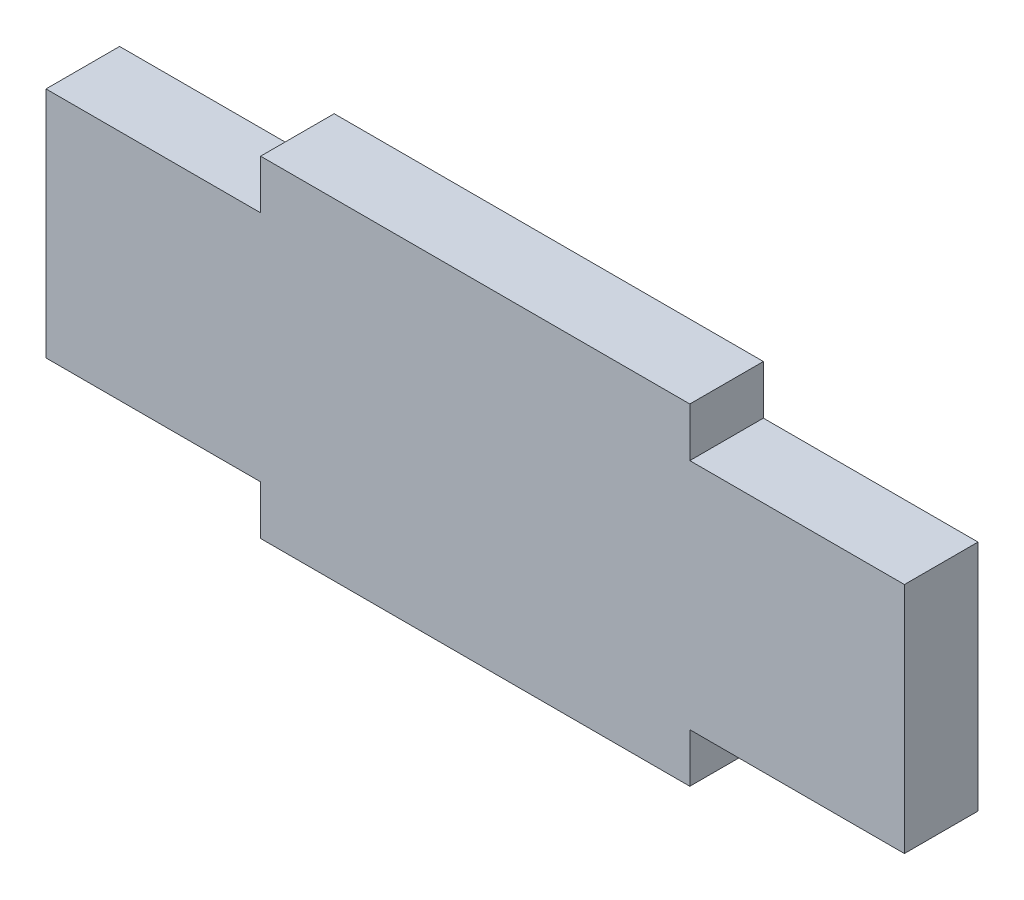
SolidWorks part; units mm, degrees
material "Acrílico (médio-alto impacto)"
ref_plane "Plano frontal" through (0, 0, 0) normal (0, 0, 1) x (1, 0, 0)
ref_plane "Plano superior" through (0, 0, 0) normal (0, 1, 0) x (1, 0, 0)
ref_plane "Plano direito" through (0, 0, 0) normal (1, 0, 0) x (0, 0, -1)
sketch "Esboço1" plane through (0, 0, 0) normal (0, 0, 1) x (1, 0, 0)
  line L0 (0, 0) -> (35, 0) construction
  line L1 (-35, -9.5) -> (35, -9.5)
  line L2 (-35, -9.5) -> (-35, 9.5)
  line L3 (-35, 9.5) -> (35, 9.5)
  line L4 (35, -9.5) -> (35, 9.5)
  line L5 (-35, -9.5) -> (35, 9.5) construction
  line L6 (-35, 9.5) -> (35, -9.5) construction
  line L7 (17.5, 13.5) -> (-17.5, 13.5)
  line L8 (17.5, 13.5) -> (17.5, 9.5)
  line L9 (17.5, 9.5) -> (-17.5, 9.5)
  line L10 (-17.5, 13.5) -> (-17.5, 9.5)
  line L11 (17.5, 13.5) -> (-17.5, 9.5) construction
  line L12 (17.5, 9.5) -> (-17.5, 13.5) construction
  line L13 (17.5, -9.5) -> (-17.5, -9.5)
  line L14 (-17.5, -13.5) -> (-17.5, -9.5)
  line L15 (17.5, -13.5) -> (-17.5, -13.5)
  line L16 (17.5, -13.5) -> (17.5, -9.5)
  point P0 (0, 0)
  point P6 (0, 11.5)
  dimension "D1" = 4
  dimension "D2" = 35
  dimension "D3" = 19
  dimension "D4" = 70
extrude "Ressalto-extrusão1" add sketch "Esboço1" along normal blind 6 contours L1 L4 L3 L2 | L7 L10 L3 L8 | L15 L16 L1 L14
